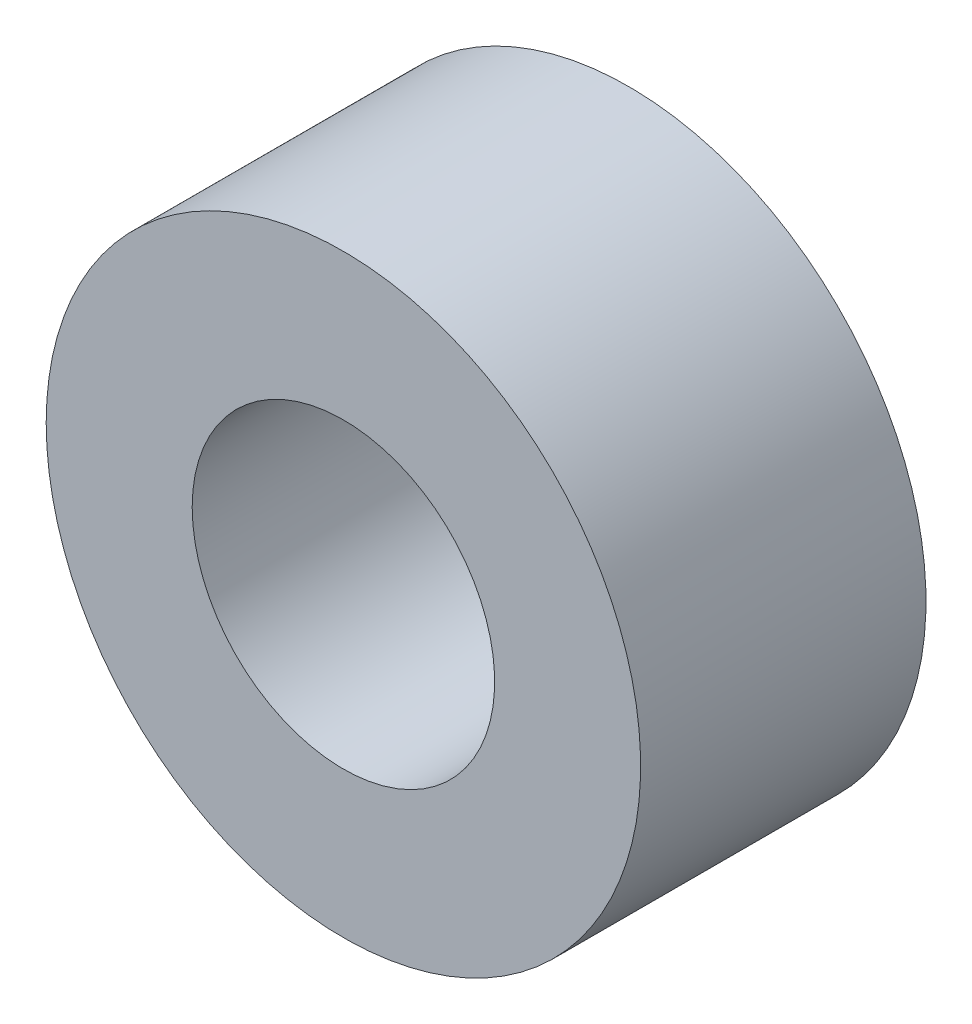
SolidWorks part; units mm, degrees
ref_plane "Front Plane" through (0, 0, 0) normal (0, 0, 1) x (1, 0, 0)
ref_plane "Top Plane" through (0, 0, 0) normal (0, 1, 0) x (1, 0, 0)
ref_plane "Right Plane" through (0, 0, 0) normal (1, 0, 0) x (0, 0, -1)
sketch "Sketch1" plane through (0, 0, 0) normal (0, 0, 1) x (1, 0, 0)
  circle A0 centre (0, 0) radius 4.0386
  circle A1 centre (0, 0) radius 7.9375
extrude "Boss-Extrude1" add sketch "Sketch1" along normal blind 7.62
